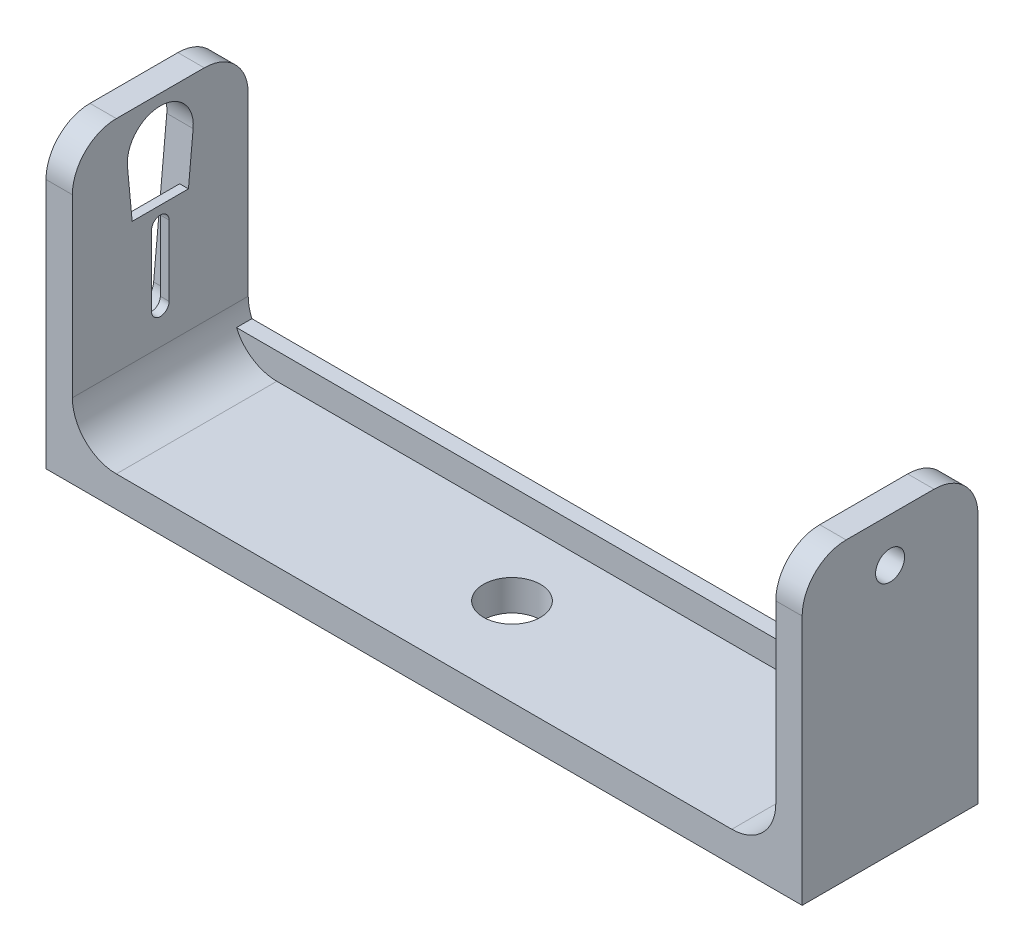
SolidWorks part; units mm, degrees
ref_plane "前视基准面" through (0, 0, 0) normal (0, 0, 1) x (1, 0, 0)
ref_plane "上视基准面" through (0, 0, 0) normal (0, 1, 0) x (1, 0, 0)
ref_plane "右视基准面" through (0, 0, 0) normal (1, 0, 0) x (0, 0, -1)
sketch "草图1" plane through (0, 0, 0) normal (0, 1, 0) x (1, 0, 0)
  line L1 (-43, 10) -> (43, 10)
  line L2 (-43, 10) -> (-43, -10)
  line L3 (-43, -10) -> (43, -10)
  line L4 (43, 10) -> (43, -10)
  line L5 (-43, 10) -> (43, -10) construction
  line L6 (-43, -10) -> (43, 10) construction
  point P0 (0, 0)
  dimension "D1" = 86
  dimension "D2" = 20
extrude "凸台-拉伸1" add sketch "草图1" along normal blind 3.5
sketch "草图2" plane through (0, 3.5, 0) normal (0, 1, 0) x (1, 0, 0)
  circle A0 centre (0, 0) radius 3.25
  dimension "D1" = 6.5
extrude "切除-拉伸1" cut sketch "草图2" against normal blind 3.5
sketch "草图3" plane through (0, 3.5, 0) normal (0, 1, 0) x (1, 0, 0)
  line L1 (40, 10) -> (43, 10)
  line L2 (40, 10) -> (40, -10)
  line L3 (40, -10) -> (43, -10)
  line L4 (43, 10) -> (43, -10)
  line L5 (40, 10) -> (43, -10) construction
  line L6 (40, -10) -> (43, 10) construction
  line L7 (-40, 10) -> (-43, 10)
  line L8 (-40, 10) -> (-40, -10)
  line L9 (-40, -10) -> (-43, -10)
  line L10 (-43, 10) -> (-43, -10)
  line L11 (-40, 10) -> (-43, -10) construction
  line L12 (-40, -10) -> (-43, 10) construction
  point P0 (41.5, 0)
  point P5 (-41.5, 0)
  dimension "D1" = 3
  dimension "D2" = 3
  dimension "D3" = 20
  dimension "D4" = 20
extrude "凸台-拉伸2" add sketch "草图3" along normal blind 30
fillet "圆角1" radius 5 1 edges at (-40, 3.5, 0)
fillet "圆角2" radius 5 1 edges at (40, 3.5, 0)
sketch "草图4" plane through (-43, 0, 0) normal (-1, 0, 0) x (0, 0, 1)
  line L0 (-10, 0) -> (10, 0) construction
  line L1 (0, 0) -> (0, 50000) construction
  circle A0 centre (0, 28.5) radius 1.65
  point P6 (0, 0)
  dimension "D1" = 3.3
  dimension "D2" = 28.5
extrude "切除-拉伸2" cut sketch "草图4" against normal blind 91
fillet "圆角3" radius 5 4 edges at (41.5, 33.5, -10) (41.5, 33.5, 10) (-41.5, 33.5, -10) (-41.5, 33.5, 10)
sketch "草图6" plane through (-43, 0, 0) normal (-1, 0, 0) x (0, 0, 1)
  line L0 (3.7335, 28.1484) -> (2.2401, 12.2891)
  line L1 (-3.7666, 28.5) -> (-2.2401, 12.2891)
  arc A0 (3.7335, 28.1484) -> (-3.7335, 28.1484) centre (0, 28.5) ccw
  circle A1 centre (0, 28.5) radius 1.65 construction
  arc A2 (-2.2401, 12.2891) -> (2.2401, 12.2891) centre (0, 12.5) ccw
  circle M5 centre (0, 28.5) radius 1.65
  dimension "D1" = 7.5
  dimension "D2" = 4.5
  dimension "D3" = 16
extrude "切除-拉伸3" cut sketch "草图6" against normal blind 2 contours L1 A2 L0 A0 M5
sketch "草图7" plane through (-41, 0, 0) normal (-1, 0, 0) x (0, 0, 1)
  line L0 (-3.1994, 22.4769) -> (3.1994, 22.4769)
  line L1 (-3.7335, 28.1484) -> (-2.2401, 12.2891) construction
  line L2 (3.7335, 28.1484) -> (2.2401, 12.2891) construction
  line L3 (3.1994, 22.4769) -> (3.7335, 28.1484)
  line L4 (-3.7335, 28.1484) -> (-3.1994, 22.4769)
  line L5 (0, 20.5) -> (0, 12.5) construction
  line L6 (1, 20.5) -> (1, 12.5)
  line L7 (-1, 20.5) -> (-1, 12.5)
  circle A0 centre (0, 28.5) radius 3.75
  arc A1 (1, 20.5) -> (-1, 20.5) centre (0, 20.5) ccw
  arc A2 (-1, 12.5) -> (1, 12.5) centre (0, 12.5) ccw
  arc A4 (-2.2401, 12.2891) -> (2.2401, 12.2891) centre (0, 12.5) ccw construction
  point P14 (0, 16.5)
  circle M5 centre (0, 28.5) radius 1.65
  line M6 (-3.7335, 28.1484) -> (-2.2401, 12.2891)
  line M8 (2.2401, 12.2891) -> (3.7335, 28.1484)
  arc M9 (3.7335, 28.1484) -> (-3.7335, 28.1484) centre (0, 28.5) ccw
  dimension "D1" = 2
  dimension "D2" = 8
extrude "切除-拉伸4" cut sketch "草图7" against normal blind 1 contours A0 M9 M5 | A0 L0 M6 M8 | L7 A2 L6 A1
sketch "草图8" plane through (0, 3.5, 0) normal (0, 1, 0) x (1, 0, 0)
  line L0 (-40, -10) -> (-40, -5) construction
  line L1 (-40, 10) -> (40.3071, 10)
  line L2 (-40, 10) -> (-40, 8.25)
  line L3 (-40, 8.25) -> (40.3071, 8.25)
  line L4 (40.3071, 10) -> (40.3071, 8.25)
  point P7 (0, 0)
  dimension "D1" = 8.25
extrude "凸台-拉伸3" add sketch "草图8" along normal blind 3
